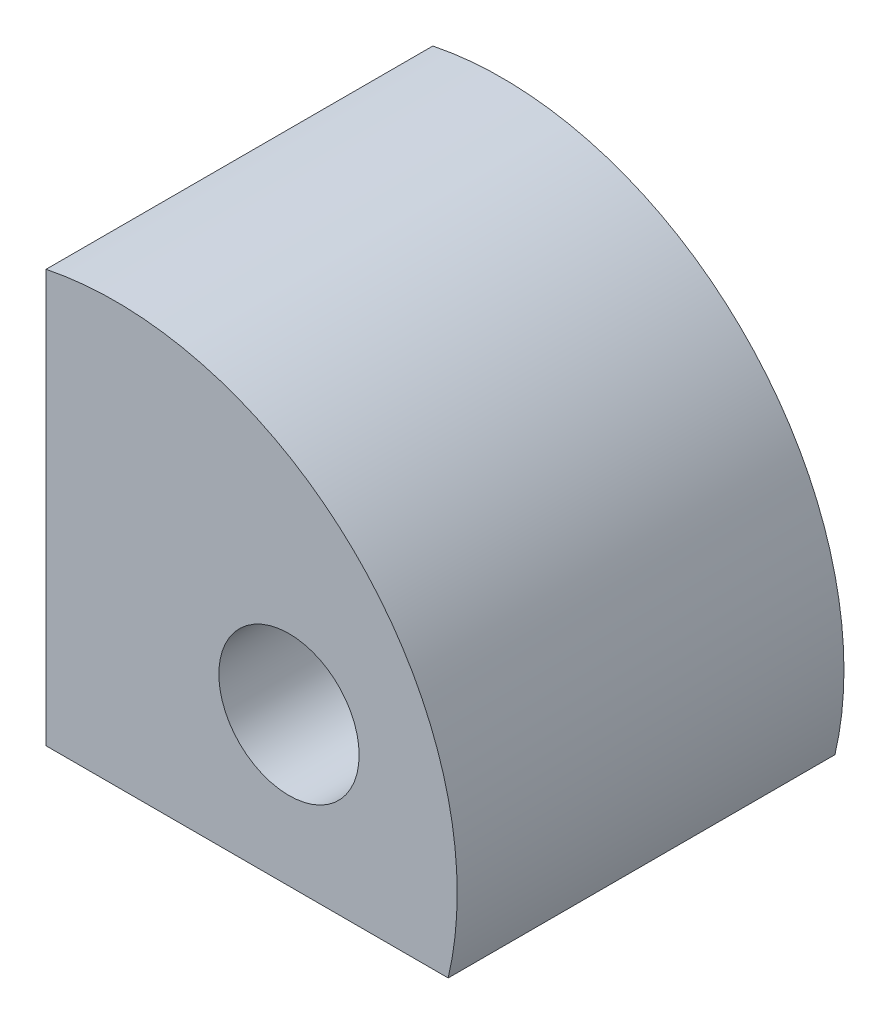
SolidWorks part; units mm, degrees
ref_plane "Front Plane" through (0, 0, 0) normal (0, 0, 1) x (1, 0, 0)
ref_plane "Top Plane" through (0, 0, 0) normal (0, 1, 0) x (1, 0, 0)
ref_plane "Right Plane" through (0, 0, 0) normal (1, 0, 0) x (0, 0, -1)
sketch "Sketch1" plane through (0, 0, 0) normal (0, 0, 1) x (1, 0, 0)
  line L22 (6.8525, -4.749) -> (-2.8942, -4.749)
  line L23 (-2.8942, 5.2522) -> (-2.8942, -4.749)
  circle A8 centre (2.9937, -1.149) radius 1.7
  arc A11 (6.8525, -4.749) -> (-2.8942, 5.2522) centre (-1.2151, -2.8614) ccw
  dimension "D2" = 9.7467
  dimension "D3" = 3.4
  dimension "D4" = 3.8588
  dimension "D1" = 3.6
  dimension "D5" = 10.0012
extrude "Boss-Extrude1" add sketch "Sketch1" along normal blind 9.3733
